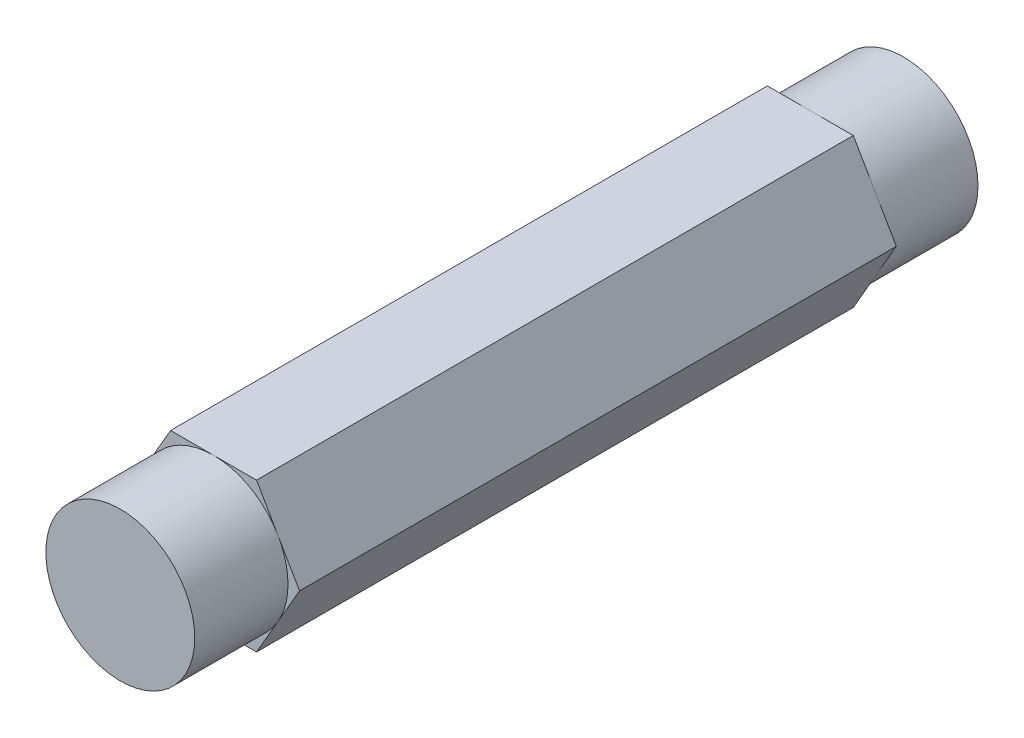
SolidWorks part; units mm, degrees
ref_plane "Front Plane" through (0, 0, 0) normal (0, 0, 1) x (1, 0, 0)
ref_plane "Top Plane" through (0, 0, 0) normal (0, 1, 0) x (1, 0, 0)
ref_plane "Right Plane" through (0, 0, 0) normal (1, 0, 0) x (0, 0, -1)
sketch "Sketch1" plane through (0, 0, 0) normal (0, 0, 1) x (1, 0, 0)
  line L1 (7.3323, 0) -> (3.6662, 6.35)
  line L2 (3.6662, 6.35) -> (-3.6662, 6.35)
  line L3 (-3.6662, 6.35) -> (-7.3323, 0)
  line L4 (-7.3323, 0) -> (-3.6662, -6.35)
  line L5 (-3.6662, -6.35) -> (3.6662, -6.35)
  line L6 (3.6662, -6.35) -> (7.3323, 0)
  circle A0 centre (0, 0) radius 6.35 construction
  dimension "D1" = 12.7
extrude "Boss-Extrude1" add sketch "Sketch1" along normal mid plane 66.802
sketch "Sketch4" plane through (0, 0, 33.401) normal (0, 0, 1) x (1, 0, 0)
  circle A0 centre (0, 0) radius 6.35
extrude "Cut-Extrude2" cut sketch "Sketch4" against normal blind 7.9502 flip side to cut
mirror "Mirror1" about plane through (0, 0, 0) normal (0, 0, 1) of "Cut-Extrude2"
equation "\"D1@Boss-Extrude1\"=1.625+.313+0.005+1/4+0.0625"
